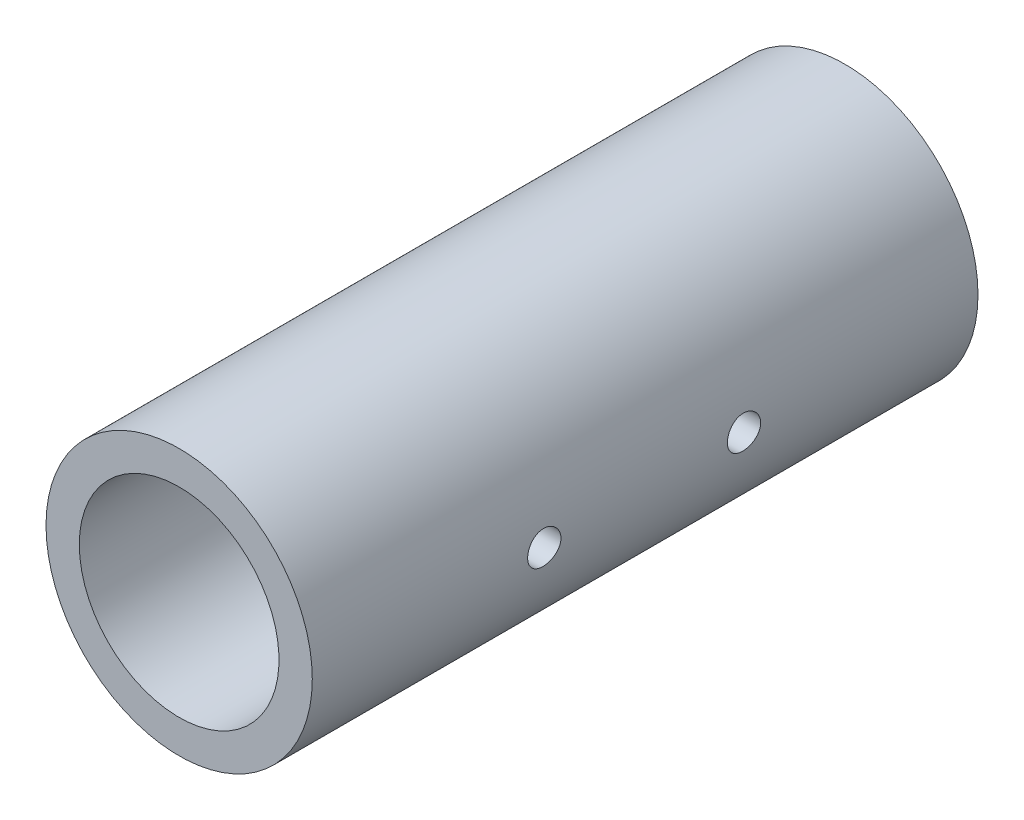
SolidWorks part; units mm, degrees
ref_plane "Front Plane" through (0, 0, 0) normal (0, 0, 1) x (1, 0, 0)
ref_plane "Top Plane" through (0, 0, 0) normal (0, 1, 0) x (1, 0, 0)
ref_plane "Right Plane" through (0, 0, 0) normal (1, 0, 0) x (0, 0, -1)
sketch "Sketch1" plane through (0, 0, 0) normal (0, 0, 1) x (1, 0, 0)
  circle A0 centre (0, 0) radius 20
  dimension "D1" = 40
extrude "Boss-Extrude1" add sketch "Sketch1" along normal blind 100
sketch "Sketch2" plane through (0, 0, 0) normal (0, 0, -1) x (-1, 0, 0)
  circle A0 centre (0, 0) radius 15
  dimension "D1" = 30
extrude "Cut-Extrude1" cut sketch "Sketch2" against normal blind 100
sketch "Sketch6" plane through (0, 0, 0) normal (1, 0, 0) x (0, 0, -1)
  line L0 (-50, 33.0046) -> (-50, -33.7849) construction
  line L1 (-65.1432, -0.3901) -> (-35.1432, -0.3901)
  circle A0 centre (-65.1432, -0.3901) radius 2.5
  circle A1 centre (-35.1432, -0.3901) radius 2.5
  point P4 (-50.1432, -0.3901)
  dimension "D2" = 5
  dimension "D3" = 5
  dimension "D1" = 15
extrude "Cut-Extrude5" cut sketch "Sketch6" against normal through all both and the other way through all contours A0 | A1
